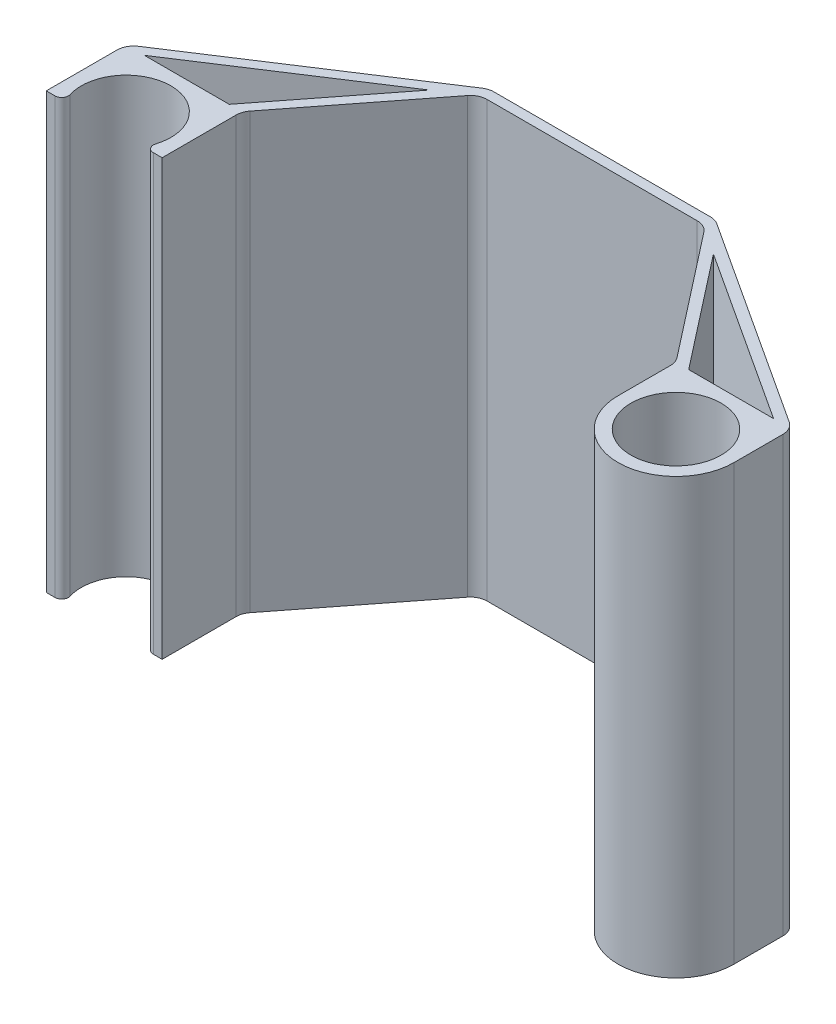
SolidWorks part; units mm, degrees
ref_plane "Front Plane" through (0, 0, 0) normal (0, 0, 1) x (1, 0, 0)
ref_plane "Top Plane" through (0, 0, 0) normal (0, 1, 0) x (1, 0, 0)
ref_plane "Right Plane" through (0, 0, 0) normal (1, 0, 0) x (0, 0, -1)
sketch "Sketch1" plane through (0, 0, 0) normal (0, 1, 0) x (1, 0, 0)
  line L0 (0, 0) -> (-34, 0)
  line L1 (-34, 0) -> (-100, -43)
  line L2 (-100, -43) -> (-100, -66.97)
  line L3 (-100, -66.97) -> (-97.3586, -66.97)
  line L4 (-67.8414, -66.97) -> (-65.2, -66.97)
  line L5 (-65.2, -66.97) -> (-65.2, -43)
  line L6 (-69.0047, -43) -> (-94.5043, -43)
  line L7 (-94.5043, -43) -> (-42.6567, -9.2205)
  line L8 (-34, -3) -> (0, -3)
  line L9 (0, -3) -> (0, 0)
  line L10 (-69.0047, -43) -> (-42.6567, -9.2205)
  line L11 (-34, -3) -> (-65.2, -43)
  arc A0 (-95.4481, -64.3784) -> (-69.7519, -64.3784) centre (-82.6, -60.4) cw
  arc A1 (-67.8414, -66.97) -> (-69.7519, -64.3784) centre (-67.8414, -64.97) cw
  arc A2 (-95.4481, -64.3784) -> (-97.3586, -66.97) centre (-97.3586, -64.97) cw
  dimension "D3" = 13.45
  dimension "D11" = 2
  dimension "D1" = 100
  dimension "D2" = 34.8
  dimension "D4" = 17.4
  dimension "D5" = 23.97
  dimension "D6" = 3
  dimension "D7" = 43
  dimension "D8" = 3
  dimension "D9" = 3
  dimension "D10" = 3
  dimension "D12" = 66
extrude "Boss-Extrude1" add sketch "Sketch1" along normal blind 130.5 contours L5 L11 L8 L9 L0 L1 L2 L3 A2 A0 A1 L4
mirror "Mirror1" about plane through (0, 130.5, 3) normal (-1, 0, 0) of "Boss-Extrude1"
sketch "Sketch4" plane through (0, 0, 0) normal (0, -1, 0) x (1, 0, 0)
  line L5 (100, 43) -> (100, 66.97) construction
  line L6 (65.2, 43) -> (100, 43)
  line L7 (65.2, 43) -> (65.2, 77.8)
  line L8 (65.2, 77.8) -> (100, 77.8)
  line L9 (100, 43) -> (100, 77.8)
  circle A0 centre (82.6, 60.4) radius 13.45
  arc A1 (69.7519, 64.3784) -> (95.4481, 64.3784) centre (82.6, 60.4) ccw construction
extrude "Boss-Extrude2" add sketch "Sketch4" against normal up to vertex (130.5 mm away) up to point (100, 130.5, 66.97)
fillet "Fillet1" radius 5 8 edges at (-100, 65.25, 43) (-34, 65.25, 0) (34, 65.25, 0) (100, 65.25, 43) (65.2, 65.25, 43) (34, 65.25, 3) (-34, 65.25, 3) (-65.2, 65.25, 43)
sketch "Sketch5" plane through (0, 0, 0) normal (0, -1, 0) x (1, 0, 0)
  line L0 (65.2, 77.8) -> (65.2, 44.7194) construction
  line L1 (65.2, 60.4) -> (65.2, 77.8)
  line L3 (100, 77.8) -> (100, 60.4)
  line L4 (65.2, 77.8) -> (83.0702, 82.4044)
  line L5 (83.0702, 82.4044) -> (100, 77.8)
  arc A0 (100, 60.4) -> (65.2, 60.4) centre (82.6, 60.4) ccw
extrude "Cut-Extrude4" cut sketch "Sketch5" against normal through all
sketch "Sketch6" plane through (0, 0, 0) normal (0, -1, 0) x (1, 0, 0)
  circle A0 centre (82.6, 60.4) radius 13.55
  dimension "D1" = 27.1
extrude "Cut-Extrude5" cut sketch "Sketch6" against normal through all
